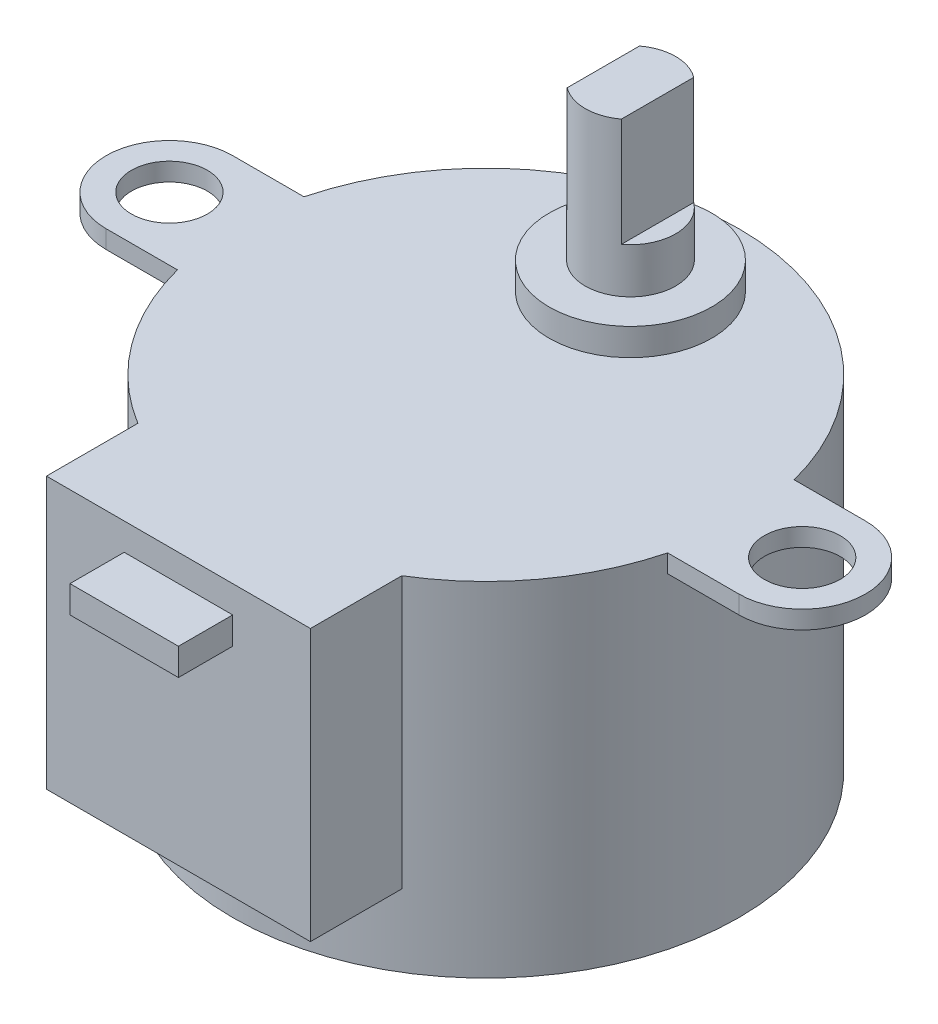
SolidWorks part; units mm, degrees
ref_plane "Front Plane" through (0, 0, 0) normal (0, 0, 1) x (1, 0, 0)
ref_plane "Top Plane" through (0, 0, 0) normal (0, 1, 0) x (1, 0, 0)
ref_plane "Right Plane" through (0, 0, 0) normal (1, 0, 0) x (0, 0, -1)
sketch "Sketch1" plane through (0, 0, 0) normal (0, 1, 0) x (1, 0, 0)
  line L0 (-17.5, 0) -> (0, 0) construction
  line L1 (0, 0) -> (17.5, 0) construction
  line L2 (-17.5, 0) -> (17.5, 0) construction
  line L3 (-17.5, 3.5) -> (-13.5554, 3.5)
  line L4 (-17.5, -3.5) -> (-13.5554, -3.5)
  line L5 (13.5554, 3.5) -> (17.5, 3.5)
  line L7 (-7.3, -11.9461) -> (-7.3, -17)
  line L8 (-7.3, -17) -> (7.3, -17)
  line L9 (7.3, -11.9461) -> (7.3, -17)
  line L10 (13.5554, -3.5) -> (17.5, -3.5)
  arc A0 (-13.5554, -3.5) -> (-7.3, -11.9461) centre (0, 0) ccw
  circle A1 centre (-17.5, 0) radius 2.1
  circle A2 centre (17.5, 0) radius 2.1
  arc A3 (-17.5, 3.5) -> (-17.5, -3.5) centre (-17.5, 0) ccw
  arc A4 (17.5, -3.5) -> (17.5, 3.5) centre (17.5, 0) ccw
  arc A5 (13.5554, 3.5) -> (-13.5554, 3.5) centre (0, 0) ccw
  arc A6 (7.3, -11.9461) -> (13.5554, -3.5) centre (0, 0) ccw
  point P7 (0, 0)
  dimension "D3" = 28
  dimension "D4" = 4.2
  dimension "D5" = 4.2
  dimension "D1" = 17.5
  dimension "D2" = 17.5
  dimension "D6" = 7
  dimension "D7" = 17
  dimension "D8" = 14.6
extrude "Boss-Extrude1" add sketch "Sketch1" along normal blind 1
sketch "Sketch2" plane through (0, 0, 0) normal (0, 1, 0) x (1, 0, 0)
  line L1 (-7.3, -17) -> (7.3, -17)
  line L2 (-7.3, -17) -> (-7.3, -11.9461)
  line L4 (7.3, -17) -> (7.3, -11.9461)
  arc A0 (7.3, -11.9461) -> (-7.3, -11.9461) centre (0, 0) ccw
extrude "Boss-Extrude2" add sketch "Sketch2" against normal blind 14
sketch "Sketch3" plane through (0, -14, 0) normal (0, -1, 0) x (1, 0, 0)
  circle A0 centre (0, 0) radius 14
extrude "Boss-Extrude3" add sketch "Sketch3" along normal blind 4
sketch "Sketch4" plane through (0, 1, 0) normal (0, 1, 0) x (1, 0, 0)
  circle A0 centre (0, 8) radius 4.5
  dimension "D2" = 9
  dimension "D1" = 8
extrude "Boss-Extrude4" add sketch "Sketch4" along normal blind 1.5
sketch "Sketch5" plane through (0, 2.5, 0) normal (0, 1, 0) x (1, 0, 0)
  circle A0 centre (0, 8) radius 2.5
  dimension "D1" = 5
extrude "Boss-Extrude5" add sketch "Sketch5" along normal blind 2.5
sketch "Sketch6" plane through (0, 5, 0) normal (0, 1, 0) x (1, 0, 0)
  line L1 (1.5, 3) -> (-1.5, 3)
  line L2 (1.5, 3) -> (1.5, 13)
  line L3 (1.5, 13) -> (-1.5, 13)
  line L4 (-1.5, 3) -> (-1.5, 13)
  line L5 (1.5, 3) -> (-1.5, 13) construction
  line L6 (1.5, 13) -> (-1.5, 3) construction
  circle A0 centre (0, 8) radius 2.5
  circle M2 centre (0, 8) radius 2.5
  dimension "D2" = 5
  dimension "D1" = 3
  dimension "D3" = 5
extrude "Boss-Extrude6" add sketch "Sketch6" along normal blind 6 contours L4 L2 M2
sketch "Sketch7" plane through (0, 0, 17) normal (0, 0, 1) x (1, 0, 0)
  line L0 (-7.3, 1) -> (7.3, 1) construction
  line L1 (3, -2) -> (-3, -2)
  line L2 (3, -2) -> (3, -0.5)
  line L3 (3, -0.5) -> (-3, -0.5)
  line L4 (-3, -2) -> (-3, -0.5)
  line L5 (3, -2) -> (-3, -0.5) construction
  line L6 (3, -0.5) -> (-3, -2) construction
  point P0 (0, -1.25)
  dimension "D1" = 6
  dimension "D2" = 1.5
  dimension "D3" = 0
  dimension "D4" = 3
extrude "Boss-Extrude7" add sketch "Sketch7" along normal blind 3
sketch "Sketch8" plane through (0, 0, 0) normal (0, 1, 0) x (1, 0, 0)
  circle A0 centre (0, 8) radius 2.5 construction
  circle A1 centre (-17.5, 0) radius 2.1 construction
  circle A2 centre (17.5, 0) radius 2.1 construction
  circle A3 centre (0, 8) radius 2.5
  circle A4 centre (-17.5, 0) radius 2.1
  circle A5 centre (17.5, 0) radius 2.1
